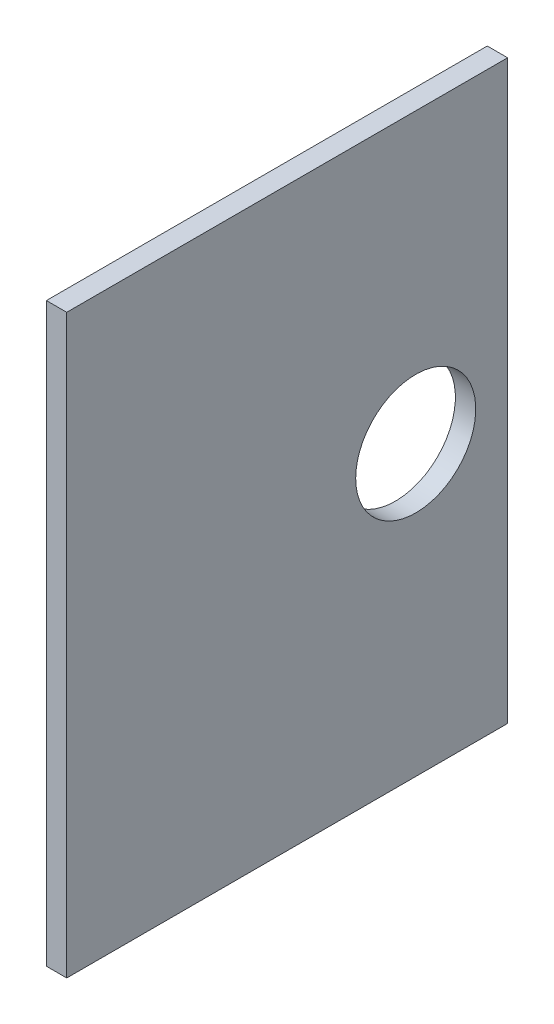
SolidWorks part; units mm, degrees
ref_plane "Front Plane" through (0, 0, 0) normal (0, 0, 1) x (1, 0, 0)
ref_plane "Top Plane" through (0, 0, 0) normal (0, 1, 0) x (1, 0, 0)
ref_plane "Right Plane" through (0, 0, 0) normal (1, 0, 0) x (0, 0, -1)
sketch "Sketch1" plane through (0, 0, 0) normal (1, 0, 0) x (0, 0, -1)
  line L0 (0, 0) -> (48.1329, 0) construction
  line L1 (-82.55, -107.95) -> (82.55, -107.95)
  line L2 (-82.55, -107.95) -> (-82.55, 107.95)
  line L3 (-82.55, 107.95) -> (82.55, 107.95)
  line L4 (82.55, -107.95) -> (82.55, 107.95)
  line L5 (-82.55, -107.95) -> (82.55, 107.95) construction
  line L6 (-82.55, 107.95) -> (82.55, -107.95) construction
  circle A0 centre (48.1329, 0) radius 22.479
  point P0 (0, 0)
  point P8 (41.3951, 0)
  point P9 (48.1329, 0)
  dimension "D1" = 44.958
  dimension "D2" = 165.1
  dimension "D3" = 215.9
extrude "Boss-Extrude1" add sketch "Sketch1" along normal blind 7.62
